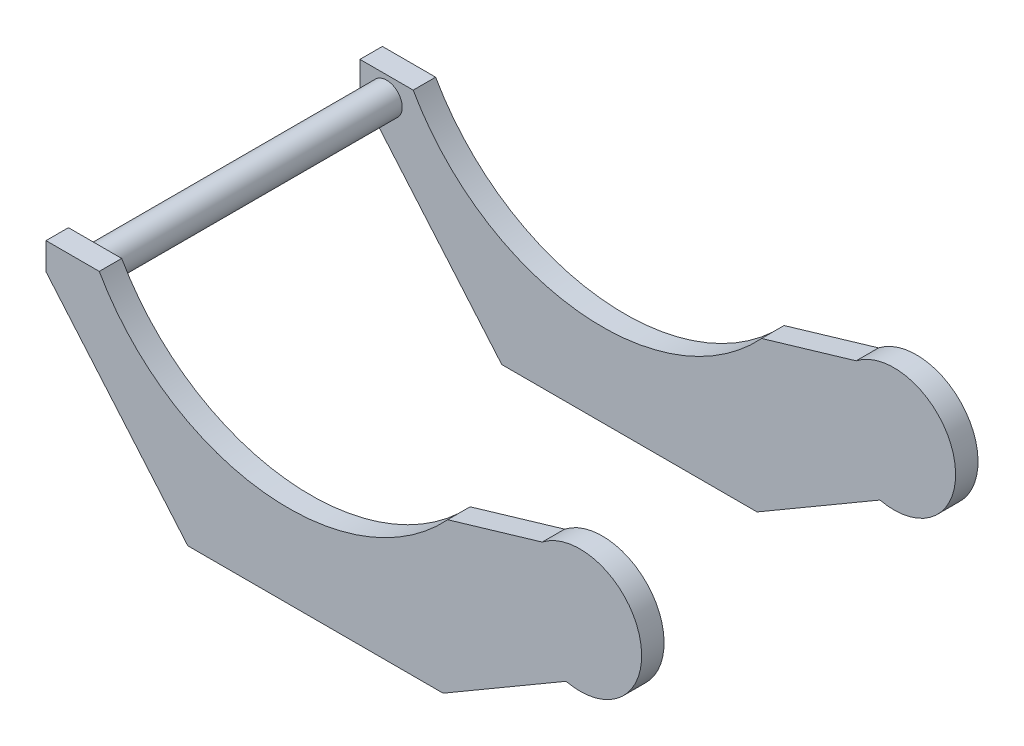
SolidWorks part; units mm, degrees
ref_plane "Front Plane" through (0, 0, 0) normal (0, 0, 1) x (1, 0, 0)
ref_plane "Top Plane" through (0, 0, 0) normal (0, 1, 0) x (1, 0, 0)
ref_plane "Right Plane" through (0, 0, 0) normal (1, 0, 0) x (0, 0, -1)
sketch "Sketch1" plane through (0, 0, 0) normal (0, 0, 1) x (1, 0, 0)
  line L0 (0, 0) -> (0, 61.0877) construction
  line L1 (-106.25, 0) -> (-96.75, 0)
  line L2 (-34.604, -7.2924) -> (-17.7389, -2.3133)
  line L3 (-13.4921, -21.6979) -> (-35.4167, -34.5)
  line L4 (-35.4167, -34.5) -> (-80.9524, -34.5)
  line L5 (-80.9524, -34.5) -> (-106.25, -4.814)
  line L6 (-106.25, -4.814) -> (-106.25, 0)
  line L7 (-87.6317, -19.7143) -> (-15.1201, -19.7143) construction
  arc A0 (-96.75, 0) -> (-34.604, -7.2924) centre (-63.0198, 18.9982) ccw
  arc A1 (-17.7389, -2.3133) -> (-13.4921, -21.6979) centre (-10.9929, -10.9929) cw
  point P10 (0, 0)
  point P14 (-39.6868, -11.8923)
  point P17 (-63.0198, -19.7143)
  dimension "D1" = 21.9857
  dimension "D2" = 34.5
  dimension "D3" = 193.5
  dimension "D4" = 106.25
  dimension "D5" = 19.7143
  dimension "D6" = 45.5357
  dimension "D7" = 25.2976
  dimension "D8" = 21.9246
  dimension "D9" = 4.814
  dimension "D10" = 16.8651
  dimension "D11" = 33.7302
  dimension "D12" = 23.6111
extrude "Boss-Extrude1" add sketch "Sketch1" along normal blind 4
pattern_linear "LPattern1" count 2 spacing 56 along (0, 0, 1) of "Boss-Extrude1"
sketch "Sketch2" plane through (0, 0, 60) normal (0, 0, 1) x (1, 0, 0)
  line L0 (-96.75, 0) -> (-106.25, 0) construction
  line L1 (-101.5, 0) -> (-101.5, -10.3879) construction
  line L2 (-106.25, -4.814) -> (-80.9524, -34.5) construction
  circle A0 centre (-101.5, -3.6265) radius 2.7894
  point P2 (0, 0)
  point P3 (-101.5, -4.0119)
  point P6 (-101.5, 0)
  point P7 (-101.5, -3.6265)
  dimension "D1" = 3.6265
  dimension "D2" = 5.5787
extrude "Boss-Extrude2" add sketch "Sketch2" against normal up to surface (56 mm away) up to face at (-59.7435, -14.6946, 4)
equation "\"D5@Sketch1\"=\"D2@Sketch1\"*2.4/4.2"
equation "\"D6@Sketch1\"=\"D4@Sketch1\"*3/7"
equation "\"D4@Sketch1\"=119*(70-7.5)/70"
equation "\"D7@Sketch1\"=\"D4@Sketch1\"*1.5/6.3"
equation "\"D8@Sketch1\"=\"D4@Sketch1\"*1.3/6.3"
equation "\"D1@Sketch1\"=57*13.5/35"
equation "\"D9@Sketch1\"=\"D2@Sketch1\"*3/21.5"
equation "\"D10@Sketch1\"=\"D4@Sketch1\"*1/6.3"
equation "\"D11@Sketch1\"=\"D4@Sketch1\"*2/6.3"
equation "\"D12@Sketch1\"=\"D4@Sketch1\"*1.4/6.3"
